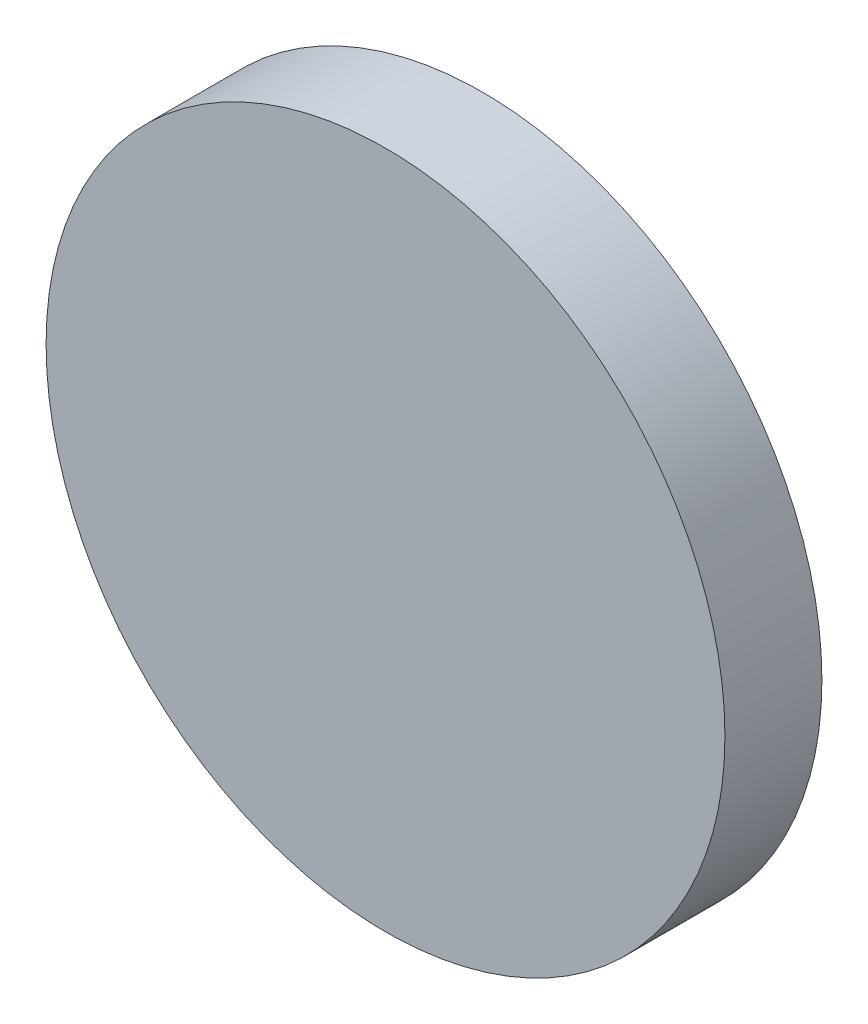
SolidWorks part; units mm, degrees
ref_plane "Płaszczyzna przednia" through (0, 0, 0) normal (0, 0, 1) x (1, 0, 0)
ref_plane "Płaszczyzna górna" through (0, 0, 0) normal (0, 1, 0) x (1, 0, 0)
ref_plane "Płaszczyzna prawa" through (0, 0, 0) normal (1, 0, 0) x (0, 0, -1)
sketch "Szkic1" plane through (0, 0, 0) normal (0, 0, 1) x (1, 0, 0)
  circle A0 centre (0, 0) radius 14
  dimension "D1" = 28
extrude "Dodanie-wyciągnięcie1" add sketch "Szkic1" along normal blind 4
